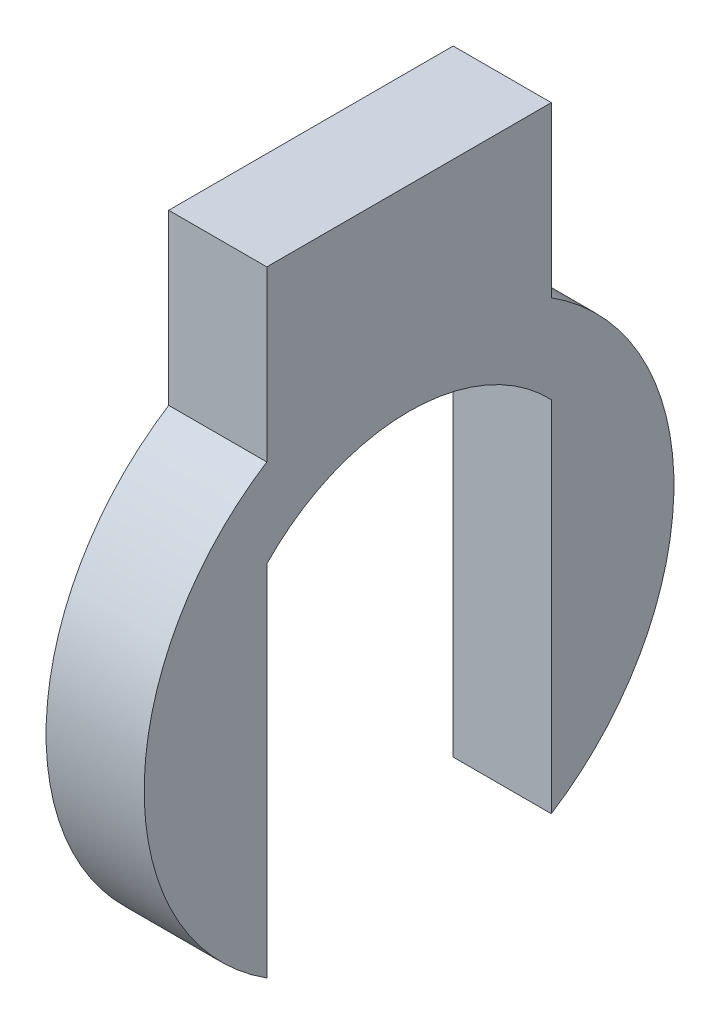
SolidWorks part; units mm, degrees
ref_plane "Front Plane" through (0, 0, 0) normal (0, 0, 1) x (1, 0, 0)
ref_plane "Top Plane" through (0, 0, 0) normal (0, 1, 0) x (1, 0, 0)
ref_plane "Right Plane" through (0, 0, 0) normal (1, 0, 0) x (0, 0, -1)
sketch "Sketch1" plane through (0, 0, 0) normal (1, 0, 0) x (0, 0, -1)
  line L1 (-3.683, -7.5664) -> (3.683, -7.5664)
  line L2 (-3.683, -7.5664) -> (-3.683, 10.16)
  line L3 (-3.683, 10.16) -> (3.683, 10.16)
  line L4 (3.683, -7.5664) -> (3.683, 10.16)
  circle A0 centre (0, 0) radius 5.08
  circle A1 centre (0, 0) radius 6.858
  point P9 (0, 10.16)
  dimension "D1" = 10.16
  dimension "D3" = 13.716
  dimension "D2" = 7.366
  dimension "D4" = 10.16
extrude "Boss-Extrude1" add sketch "Sketch1" along normal blind 2.54 contours L2 A0 | L4 A0 | L4 A1 A0 | L4 A1 L2 A0 | L2 A1 A0 | A1 L4 L3 L2
